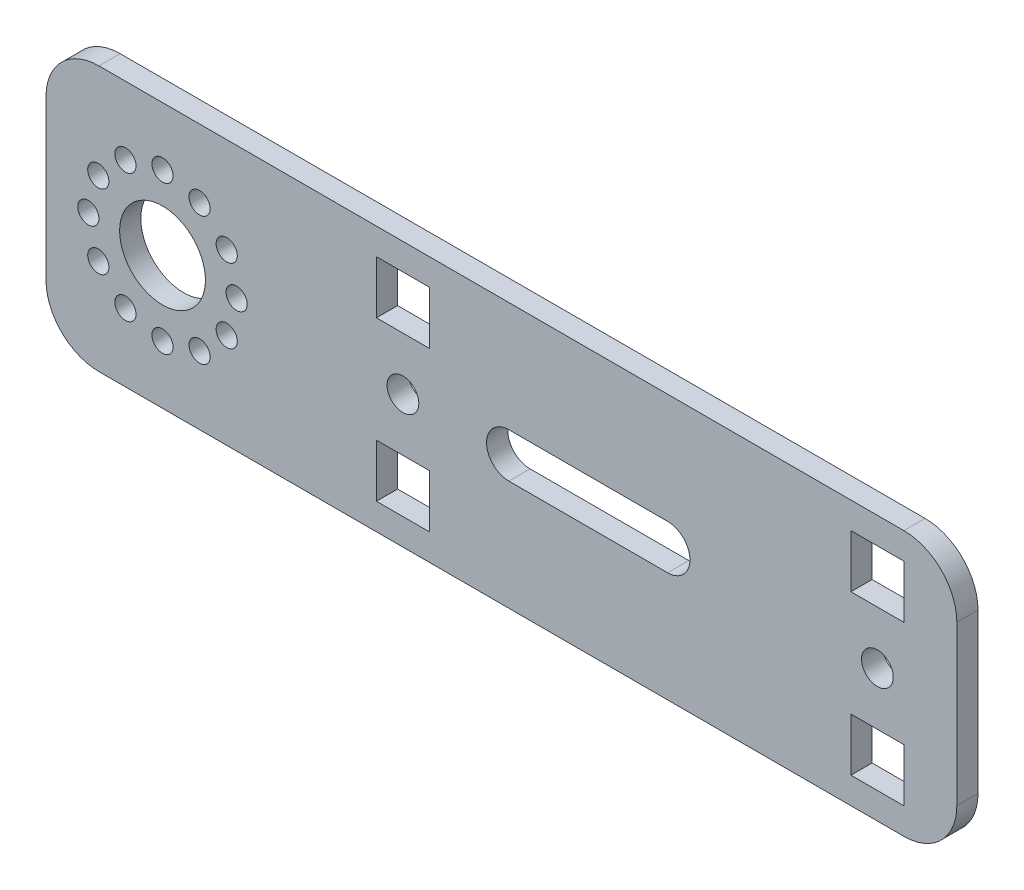
SolidWorks part; units mm, degrees
ref_plane "Plan de face" through (0, 0, 0) normal (0, 0, 1) x (1, 0, 0)
ref_plane "Plan de dessus" through (0, 0, 0) normal (0, 1, 0) x (1, 0, 0)
ref_plane "Plan de droite" through (0, 0, 0) normal (1, 0, 0) x (0, 0, -1)
sketch "Esquisse2" plane through (0, 0, 0) normal (0, 0, -1) x (-1, 0, 0)
  line L0 (-86, -12.5) -> (0, -12.5)
  line L1 (-31.2, -12.5) -> (-31.2, 12.5) construction
  line L2 (0, -12.5) -> (0, 12.5)
  line L3 (0, 12.5) -> (-86, 12.5)
  line L4 (-86, 12.5) -> (-86, -12.5)
  line L5 (-95.5557, 0) -> (0, 0) construction
  line L6 (-76, 12.5) -> (-76, -12.5) construction
  line L7 (-43.7, 0) -> (-58.7, 0) construction
  line L8 (-43.7, -2.1) -> (-58.7, -2.1)
  line L9 (-43.7, 2.1) -> (-58.7, 2.1)
  arc A0 (-43.7, -2.1) -> (-43.7, 2.1) centre (-43.7, 0) ccw
  arc A1 (-58.7, 2.1) -> (-58.7, -2.1) centre (-58.7, 0) ccw
  point P12 (-51.2, 0)
  circle B0 centre (-11, 0) radius 4.05
  circle B1 centre (-4, 0) radius 1
  circle B2 centre (-4.9378, -3.5) radius 1
  circle B3 centre (-7.5, -6.0622) radius 1
  circle B4 centre (-11, -7) radius 1
  circle B5 centre (-14.5, -6.0622) radius 1
  circle B6 centre (-17.0622, -3.5) radius 1
  circle B7 centre (-18, 0) radius 1
  circle B8 centre (-17.0622, 3.5) radius 1
  circle B9 centre (-14.5, 6.0622) radius 1
  circle B10 centre (-11, 7) radius 1
  circle B11 centre (-7.5, 6.0622) radius 1
  circle B12 centre (-4.9378, 3.5) radius 1
  line B13 (-81, -5) -> (-81, -10)
  line B14 (-81, -5) -> (-76, -5)
  line B15 (-76, -5) -> (-76, -10)
  line B16 (-81, -10) -> (-76, -10)
  line B17 (-81, 5) -> (-81, 10)
  line B18 (-81, 5) -> (-76, 5)
  line B19 (-76, 5) -> (-76, 10)
  line B20 (-81, 10) -> (-76, 10)
  line B21 (-78.5, 0) -> (-85.4724, 0) construction
  circle B22 centre (-78.5, 0) radius 1.5
  line B23 (-33.7, -5) -> (-33.7, 5) construction
  line B24 (-36.2, -5) -> (-36.2, -10)
  line B25 (-36.2, -5) -> (-31.2, -5)
  line B26 (-31.2, -5) -> (-31.2, -10)
  line B27 (-36.2, -10) -> (-31.2, -10)
  line B28 (-36.2, 5) -> (-36.2, 10)
  line B29 (-36.2, 5) -> (-31.2, 5)
  line B30 (-31.2, 5) -> (-31.2, 10)
  line B31 (-36.2, 10) -> (-31.2, 10)
  line B32 (-33.7, 0) -> (-40.6724, 0) construction
  circle B33 centre (-33.7, 0) radius 1.5
  dimension "D8" = 2.1
  dimension "D1" = 25
  dimension "D2" = 11
  dimension "D3" = 65
  dimension "D4" = 39.8
  dimension "D5" = 5
  dimension "D6" = 10
  dimension "D7" = 15
sketch_block_instance "Block1-1"
sketch_block "Block1" parameters "D2"=2, "D3"=8.1, "D1"=7
sketch_block_instance "Trou M3 plots 5mm-1"
sketch_block "Trou M3 plots 5mm" parameters "D2"=3, "D1"=5, "D3"=5, "D4"=10
sketch_block_instance "Trou M3 plots 5mm-3"
extrude "Boss.-Extru.1" add sketch "Esquisse2" against normal blind 2
fillet "Congé1" radius 5 4 edges at (0, -12.5, 1) (0, 12.5, 1) (86, 12.5, 1) (86, -12.5, 1)
